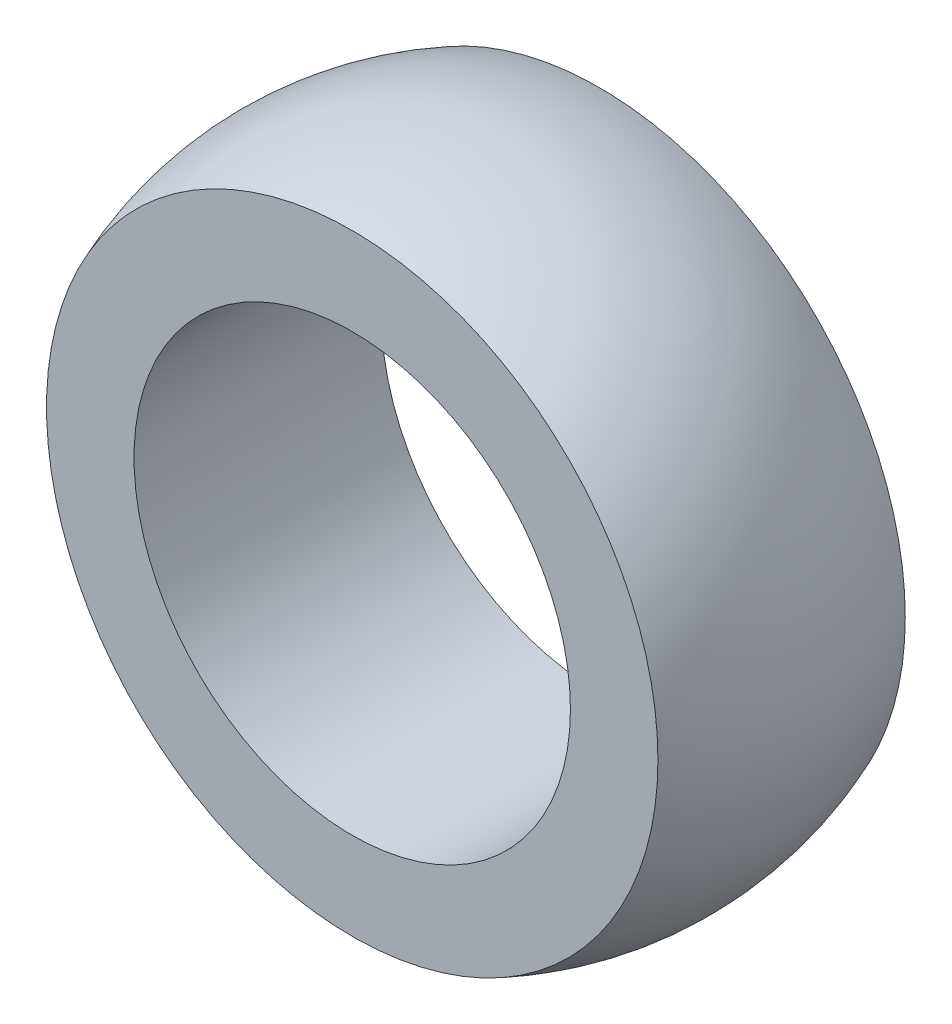
SolidWorks part; units mm, degrees
ref_plane "Front Plane" through (0, 0, 0) normal (0, 0, 1) x (1, 0, 0)
ref_plane "Top Plane" through (0, 0, 0) normal (0, 1, 0) x (1, 0, 0)
ref_plane "Right Plane" through (0, 0, 0) normal (1, 0, 0) x (0, 0, -1)
sketch "Sketch1" plane through (0, 0, 0) normal (0, 0, 1) x (1, 0, 0)
  line L0 (0, 12) -> (0, -12)
  line L1 (-12, 0) -> (12, 0) construction
  arc A0 (0, -12) -> (0, 12) centre (0, 0) ccw
  dimension "D1" = 24
revolve "Revolve1" add sketch "Sketch1" angle 360 about L0
sketch "Sketch4" plane through (0, 0, 0) normal (0, 1, 0) x (1, 0, 0)
  line L1 (14.565, -4.5) -> (-14.565, -4.5)
  line L2 (14.565, -4.5) -> (14.565, 4.5)
  line L3 (14.565, 4.5) -> (-14.565, 4.5)
  line L4 (-14.565, -4.5) -> (-14.565, 4.5)
  line L5 (14.565, -4.5) -> (-14.565, 4.5) construction
  line L6 (14.565, 4.5) -> (-14.565, -4.5) construction
  point P0 (0, 0)
  dimension "12" = 9
extrude "Cut-Extrude2" cut sketch "Sketch4" against normal through all both and the other way through all flip side to cut
sketch "Sketch5" plane through (0, 0, 4.5) normal (0, 0, 1) x (1, 0, 0)
  circle A0 centre (0, 0) radius 7.94
  dimension "D1" = 15.88
extrude "Cut-Extrude3" cut sketch "Sketch5" against normal blind 30
